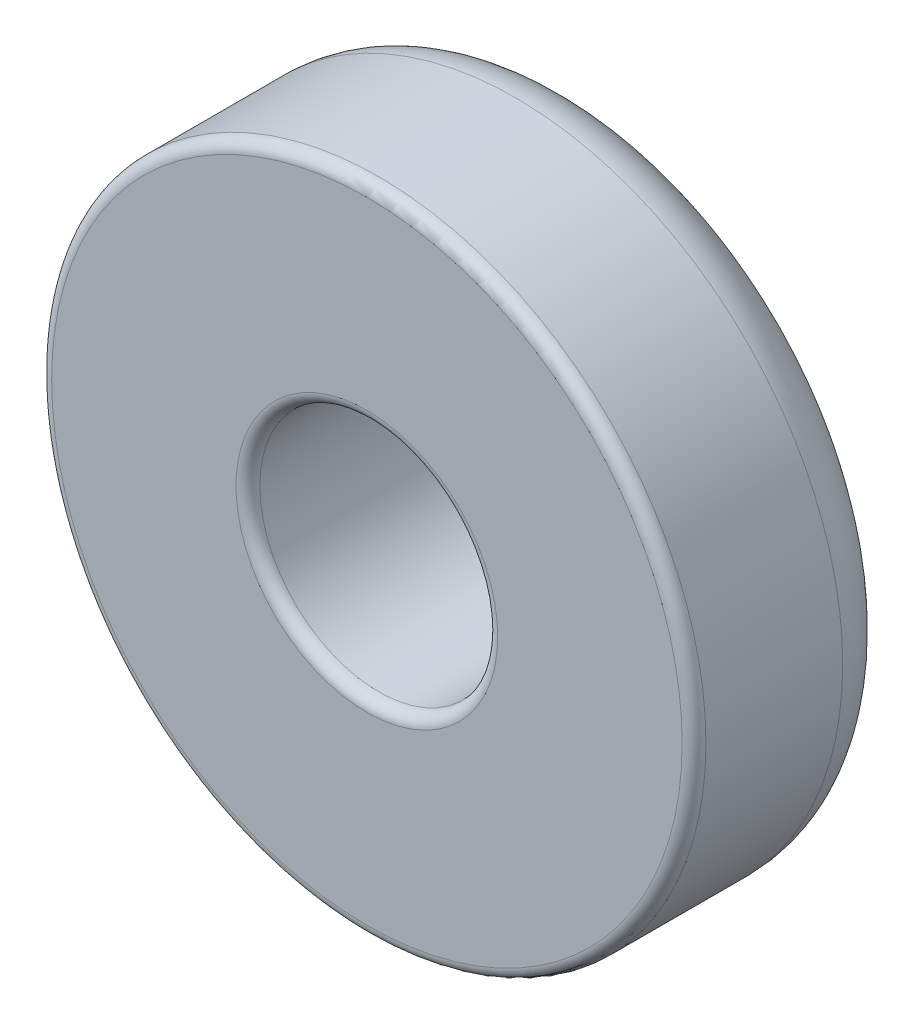
SolidWorks part; units mm, degrees
ref_plane "Front Plane" through (0, 0, 0) normal (0, 0, 1) x (1, 0, 0)
ref_plane "Top Plane" through (0, 0, 0) normal (0, 1, 0) x (1, 0, 0)
ref_plane "Right Plane" through (0, 0, 0) normal (1, 0, 0) x (0, 0, -1)
sketch "Sketch1" plane through (0, 0, 0) normal (0, 0, 1) x (1, 0, 0)
  circle A0 centre (0, 0) radius 1
  dimension "D1" = 2
extrude "Extrude-Thin1" add sketch "Sketch1" along normal blind 1.75 thin
fillet "Fillet1" radius 0.5 1 edges at (2.75, 0, 0)
fillet "Fillet2" radius 0.1 3 edges at (1, 0, 1.75) (2.75, 0, 1.75) (1, 0, 0)
